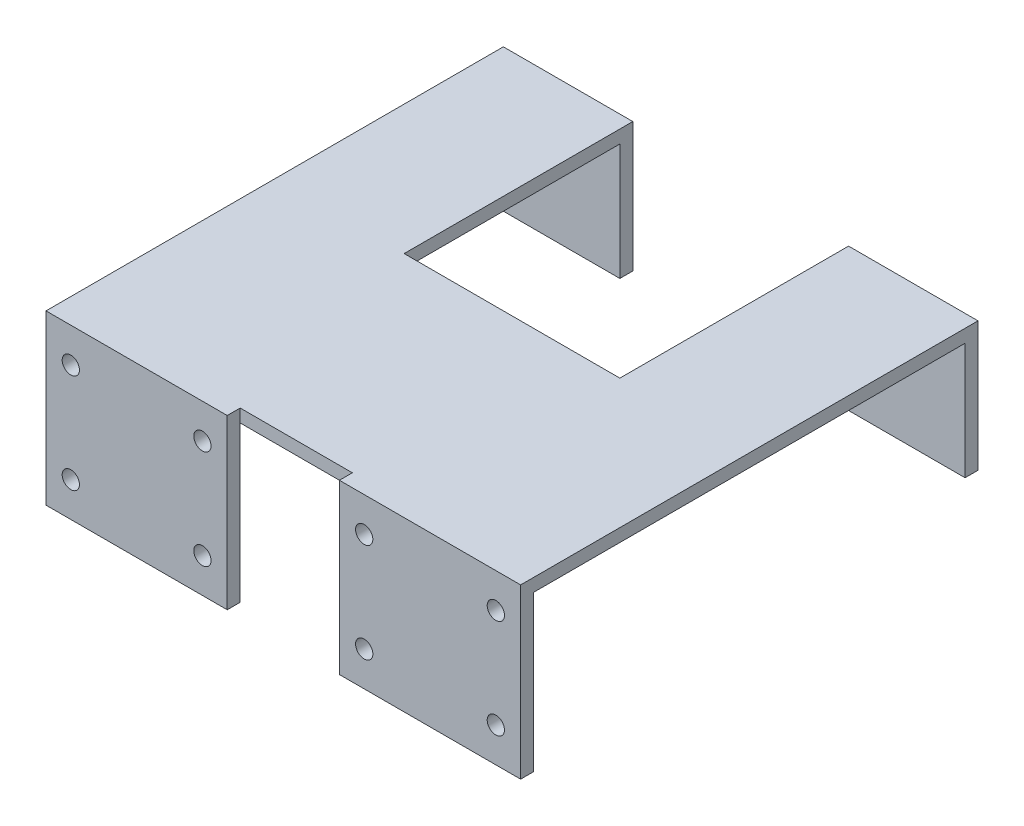
SolidWorks part; units mm, degrees
ref_plane "Front Plane" through (0, 0, 0) normal (0, 0, 1) x (1, 0, 0)
ref_plane "Top Plane" through (0, 0, 0) normal (0, 1, 0) x (1, 0, 0)
ref_plane "Right Plane" through (0, 0, 0) normal (1, 0, 0) x (0, 0, -1)
sketch "Sketch2" plane through (0, 0, 0) normal (0, 1, 0) x (1, 0, 0)
  line L0 (-55, 52.2809) -> (-55, -47.7191)
  line L1 (-55, -47.7191) -> (55, -47.7191)
  line L2 (55, -47.7191) -> (55, 52.2809)
  line L3 (55, 52.2809) -> (25, 52.2809)
  line L4 (25, 52.2809) -> (25, 2.2809)
  line L5 (25, 2.2809) -> (-25, 2.2809)
  line L6 (-25, 2.2809) -> (-25, 52.2809)
  line L7 (-25, 52.2809) -> (-55, 52.2809)
  line L8 (0, 0) -> (0, 42.7366) construction
  dimension "D1" = 110
  dimension "D2" = 100
  dimension "D3" = 30
  dimension "D4" = 30
  dimension "D5" = 50
  dimension "D6" = 25
extrude "Boss-Extrude1" add sketch "Sketch2" along normal blind 3
sketch "Sketch4" plane through (0, 0, 47.7191) normal (0, 0, 1) x (1, 0, 0)
  line L0 (0, 0) -> (0, -26.5063) construction
  line L1 (-55, 3) -> (-13, 3)
  line L2 (-55, 3) -> (-55, -36)
  line L3 (-55, -36) -> (-13, -36)
  line L4 (-13, 3) -> (-13, -36)
  line L5 (-55, 0) -> (55, 0) construction
  line L6 (55, -36) -> (13, -36)
  line L7 (13, 3) -> (13, -36)
  line L8 (55, 3) -> (13, 3)
  line L9 (55, 3) -> (55, -36)
  line L10 (55, -16.5) -> (13, -16.5) construction
  line L11 (34, -36) -> (34, -16.5) construction
  circle A0 centre (49.25, -5) radius 2
  circle A1 centre (49.25, -28) radius 2
  circle A2 centre (18.75, -5) radius 2
  circle A3 centre (18.75, -28) radius 2
  circle A4 centre (-18.75, -5) radius 2
  circle A5 centre (-49.25, -5) radius 2
  circle A6 centre (-18.75, -28) radius 2
  circle A7 centre (-49.25, -28) radius 2
  dimension "D5" = 4
  dimension "D1" = 39
  dimension "D2" = 42
  dimension "D3" = 8
  dimension "D4" = 5.75
extrude "Boss-Extrude2" add sketch "Sketch4" along normal blind 3
sketch "Sketch5" plane through (0, 0, -52.2809) normal (0, 0, -1) x (-1, 0, 0)
  line L0 (0, 0) -> (0, -36.9231) construction
  line L1 (55, 3) -> (25, 3)
  line L2 (55, 3) -> (55, -27)
  line L3 (55, -27) -> (25, -27)
  line L4 (25, 3) -> (25, -27)
  line L5 (-55, -27) -> (-25, -27)
  line L6 (-25, 3) -> (-25, -27)
  line L7 (-55, 3) -> (-25, 3)
  line L8 (-55, 3) -> (-55, -27)
  circle A0 centre (40, -12) radius 2
  circle A1 centre (-40, -12) radius 2
  dimension "D2" = 4
  dimension "D1" = 30
  dimension "D3" = 15
  dimension "D4" = 15
extrude "Boss-Extrude3" add sketch "Sketch5" along normal blind 3
